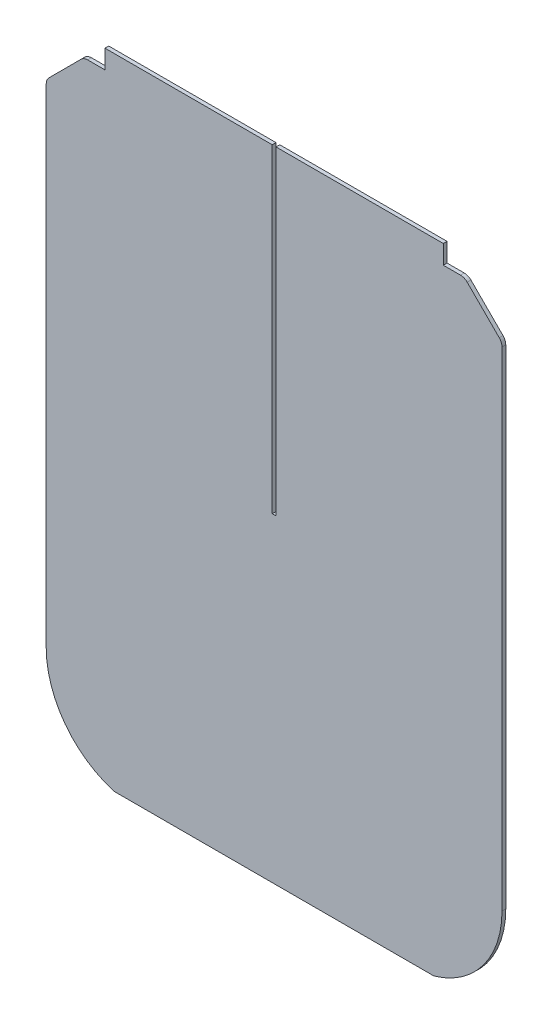
SolidWorks part; units mm, degrees
ref_plane "Front Plane" through (0, 0, 0) normal (0, 0, 1) x (1, 0, 0)
ref_plane "Top Plane" through (0, 0, 0) normal (0, 1, 0) x (1, 0, 0)
ref_plane "Right Plane" through (0, 0, 0) normal (1, 0, 0) x (0, 0, -1)
sketch "Sketch1" plane through (0, 0, 0) normal (0, 0, 1) x (1, 0, 0)
  line L0 (48.5, -48.8093) -> (48.5, 132) construction
  line L1 (14.5, 0) -> (82.5, 0)
  line L2 (0, 19.2289) -> (0, 124)
  line L3 (8, 132) -> (12.5, 132)
  line L4 (97, 19.2289) -> (97, 124)
  line L5 (12.5, 132) -> (48.5, 132) construction
  line L6 (12.5, 132) -> (12.5, 136)
  line L7 (12.5, 136) -> (48.1, 136)
  line L8 (84.5, 132) -> (84.5, 136)
  line L9 (48.5, 132) -> (84.5, 132) construction
  line L10 (84.5, 132) -> (89, 132)
  line L11 (48.5, 132) -> (84.5, 132) construction
  line L12 (12.5, 132) -> (48.5, 132) construction
  line L13 (97, 124) -> (89, 132)
  line L14 (0, 124) -> (8, 132)
  line L15 (97, 124) -> (97, 132) construction
  line L16 (89, 132) -> (97, 132) construction
  line L17 (0, 132) -> (8, 132) construction
  line L18 (0, 124) -> (0, 132) construction
  line L19 (82.5, 0) -> (97, 0) construction
  line L20 (97, 0) -> (97, 19.2289) construction
  line L21 (0, 0) -> (14.5, 0) construction
  line L22 (0, 0) -> (0, 19.2289) construction
  line L23 (48.5, 136) -> (48.9, 136) construction
  line L24 (48.1, 136) -> (48.5, 136) construction
  line L25 (48.1, 136) -> (48.1, 68)
  line L26 (48.1, 68) -> (48.9, 68)
  line L27 (48.9, 136) -> (48.9, 68)
  line L28 (48.9, 136) -> (84.5, 136)
  line L29 (48.5, 136) -> (48.9, 136) construction
  line L30 (48.5, 132) -> (48.5, 136) construction
  line L31 (48.5, 136) -> (48.5, 206.0689) construction
  line L32 (48.1, 136) -> (48.5, 136) construction
  arc A0 (0, 19.2289) -> (14.5, 0) centre (20, 19.2289) ccw
  arc A1 (82.5, 0) -> (97, 19.2289) centre (77, 19.2289) ccw
  arc A2 (14.5, 0) -> (0, 19.2289) centre (20, 19.2289) ccw construction
  arc A3 (97, 19.2289) -> (82.5, 0) centre (77, 19.2289) ccw construction
  point P17 (48.5, 68)
  dimension "D11" = 40
  dimension "D12" = 40
  dimension "D1" = 97
  dimension "D2" = 132
  dimension "D3" = 72
  dimension "D4" = 4
  dimension "D5" = 48.5
  dimension "D6" = 36
  dimension "D7" = 8
  dimension "D8" = 8
  dimension "D9" = 8
  dimension "D10" = 8
  dimension "D13" = 68
  dimension "D14" = 34
  dimension "D15" = 68
  dimension "D16" = 0.8
extrude "Boss-Extrude1" add sketch "Sketch1" along normal blind 0.8
fillet "Fillet1" radius 2 4 edges at (8, 132, 0.4) (0, 124, 0.4) (89, 132, 0.4) (97, 124, 0.4)
equation "\"D5@Sketch1\"=\"D1@Sketch1\"/2"
equation "\"D6@Sketch1\"=\"D3@Sketch1\"/2"
equation "\"D14@Sketch1\"=\"D13@Sketch1\"/2"
equation "\"D15@Sketch1\"=(\"D4@Sketch1\"+\"D2@Sketch1\")/2"
